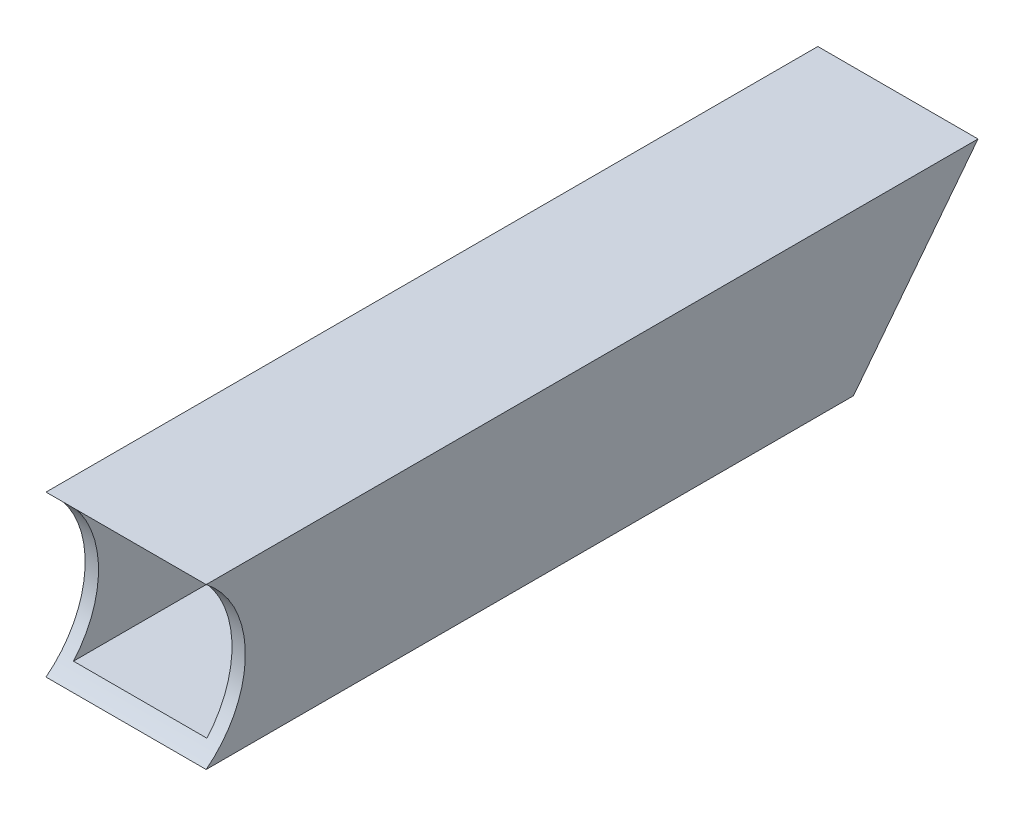
SolidWorks part; units mm, degrees
material "6063-T5"
ref_plane "Front Plane" through (0, 0, 0) normal (0, 0, 1) x (1, 0, 0)
ref_plane "Top Plane" through (0, 0, 0) normal (0, 1, 0) x (1, 0, 0)
ref_plane "Right Plane" through (0, 0, 0) normal (1, 0, 0) x (0, 0, -1)
sketch "Sketch1" plane through (0, 0, 0) normal (1, 0, 0) x (0, 0, -1)
  line L0 (198.407, 38.1) -> (168.7858, 0)
  line L1 (0, 0) -> (198.407, 0)
  line L2 (0, 0) -> (0, 38.1)
  line L3 (0, 38.1) -> (198.407, 38.1)
  line L4 (198.407, 0) -> (198.407, 38.1)
  circle A0 centre (0, 19.05) radius 24.13
  dimension "D3" = 48.26
  dimension "D1" = 38.1
  dimension "D2" = 198.407
  dimension "D4" = 48.26
extrude "Boss-Extrude1" add sketch "Sketch1" along normal blind 38.1 contours A0 L1 L0 L3
sketch "Sketch2" plane through (0, 0, 0) normal (0, 0, 1) x (1, 0, 0)
  line L0 (3.175, 34.925) -> (3.175, 3.175)
  line L1 (3.175, 3.175) -> (34.925, 3.175)
  line L2 (34.925, 3.175) -> (34.925, 34.925)
  line L3 (34.925, 34.925) -> (3.175, 34.925)
  line L4 (0, 38.1) -> (0, 0)
  line L5 (0, 0) -> (38.1, 0)
  line L6 (38.1, 0) -> (38.1, 38.1)
  line L7 (38.1, 38.1) -> (0, 38.1)
  line L8 (0, 38.1) -> (0, 0) construction
  line L9 (0, 0) -> (38.1, 0) construction
  line L10 (38.1, 0) -> (38.1, 38.1) construction
  line L11 (38.1, 38.1) -> (0, 38.1) construction
  dimension "D1" = 0
  dimension "D2" = 3.175
extrude "Cut-Extrude1" cut sketch "Sketch2" against normal through all
